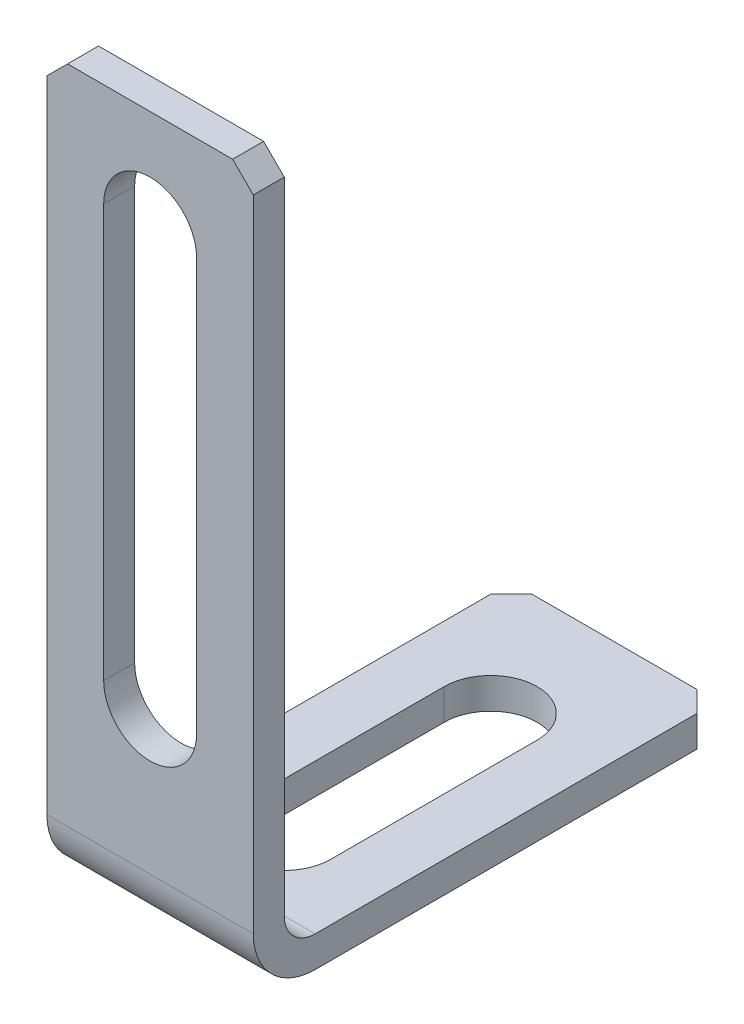
SolidWorks part; units mm, degrees
material "201 Annealed Stainless Steel (SS)"
ref_plane "Front Plane" through (0, 0, 0) normal (0, 0, 1) x (1, 0, 0)
ref_plane "Top Plane" through (0, 0, 0) normal (0, 1, 0) x (1, 0, 0)
ref_plane "Right Plane" through (0, 0, 0) normal (1, 0, 0) x (0, 0, -1)
ref_plane "Plane1" through (20, 0, 0) normal (1, 0, 0) x (0, 0, -1)
sketch "Sketch1" plane through (20, 0, 0) normal (1, 0, 0) x (0, 0, -1)
  line L0 (0, 70) -> (0, 0)
  line L1 (0, 0) -> (45, 0)
  line L2 (45, 0) -> (45, 70)
  line L3 (45, 70) -> (0, 70)
extrude "Boss-Extrude1" add sketch "Sketch1" against normal blind 20
sketch "Sketch2" plane through (0, 0, 0) normal (-1, 0, 0) x (0, 0, 1)
  line L0 (-45, 3) -> (-3, 3)
  line L1 (-3, 3) -> (-3, 70)
  line L2 (-3, 70) -> (-45, 70)
  line L3 (-45, 70) -> (-45, 3)
extrude "Cut-Extrude1" cut sketch "Sketch2" against normal through all
sketch "Sketch3" plane through (0, 3, 0) normal (0, 1, 0) x (-1, 0, 0)
  line L0 (-5.5, -33) -> (-5.5, -13)
  line L1 (-14.5, -13) -> (-14.5, -33)
  arc A0 (-14.5, -33) -> (-5.5, -33) centre (-10, -33) ccw
  arc A1 (-5.5, -13) -> (-14.5, -13) centre (-10, -13) ccw
extrude "Cut-Extrude2" cut sketch "Sketch3" against normal through all
sketch "Sketch4" plane through (0, 0, -3) normal (0, 0, -1) x (-1, 0, 0)
  line L0 (-14.5, 60) -> (-14.5, 20)
  line L1 (-5.5, 20) -> (-5.5, 60)
  arc A0 (-5.5, 60) -> (-14.5, 60) centre (-10, 60) ccw
  arc A1 (-14.5, 20) -> (-5.5, 20) centre (-10, 20) ccw
extrude "Cut-Extrude3" cut sketch "Sketch4" against normal through all
chamfer "Chamfer1" distance 2 angle 45 4 edges at (0, 70, -1.5) (0, 1.5, -45) (20, 1.5, -45) (20, 70, -1.5)
fillet "Fillet1" radius 3 1 edges at (10, 3, -3)
fillet "Fillet2" radius 6 1 edges at (10, 0, 0)
